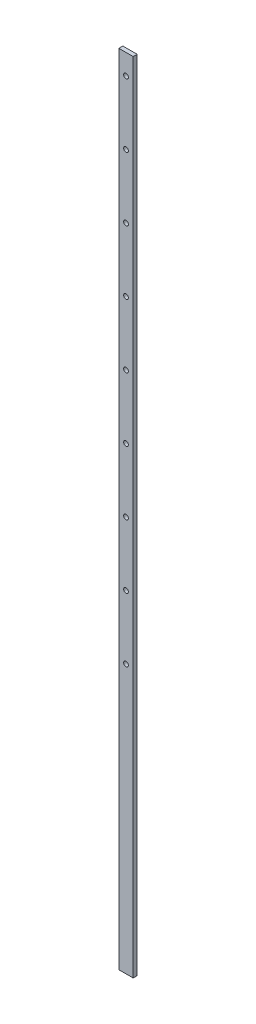
SolidWorks part; units mm, degrees
material "ASTM A36 Steel"
ref_plane "Front Plane" through (0, 0, 0) normal (0, 0, 1) x (1, 0, 0)
ref_plane "Top Plane" through (0, 0, 0) normal (0, 1, 0) x (1, 0, 0)
ref_plane "Right Plane" through (0, 0, 0) normal (1, 0, 0) x (0, 0, -1)
sketch "Sketch1" plane through (0, 0, 0) normal (0, 0, 1) x (1, 0, 0)
  line L1 (-9, -501.5) -> (9, -501.5)
  line L2 (-9, -501.5) -> (-9, 501.5)
  line L3 (-9, 501.5) -> (9, 501.5)
  line L4 (9, -501.5) -> (9, 501.5)
  line L5 (-9, -501.5) -> (9, 501.5) construction
  line L6 (-9, 501.5) -> (9, -501.5) construction
  point P0 (0, 0)
  dimension "D1" = 1003
  dimension "D2" = 18
extrude "Boss-Extrude1" add sketch "Sketch1" along normal blind 5
sketch "Sketch2" plane through (0, 0, 5) normal (0, 0, 1) x (1, 0, 0)
  line L1 (9, 501.5) -> (-9, 501.5) construction
  circle A0 centre (0, 475.82) radius 3
  dimension "D2" = 6
  dimension "D1" = 25.68
extrude "Cut-Extrude1" cut sketch "Sketch2" against normal blind 5
pattern_linear "LPattern1" count 9 spacing 80 along (0, -1, 0) of "Cut-Extrude1"
